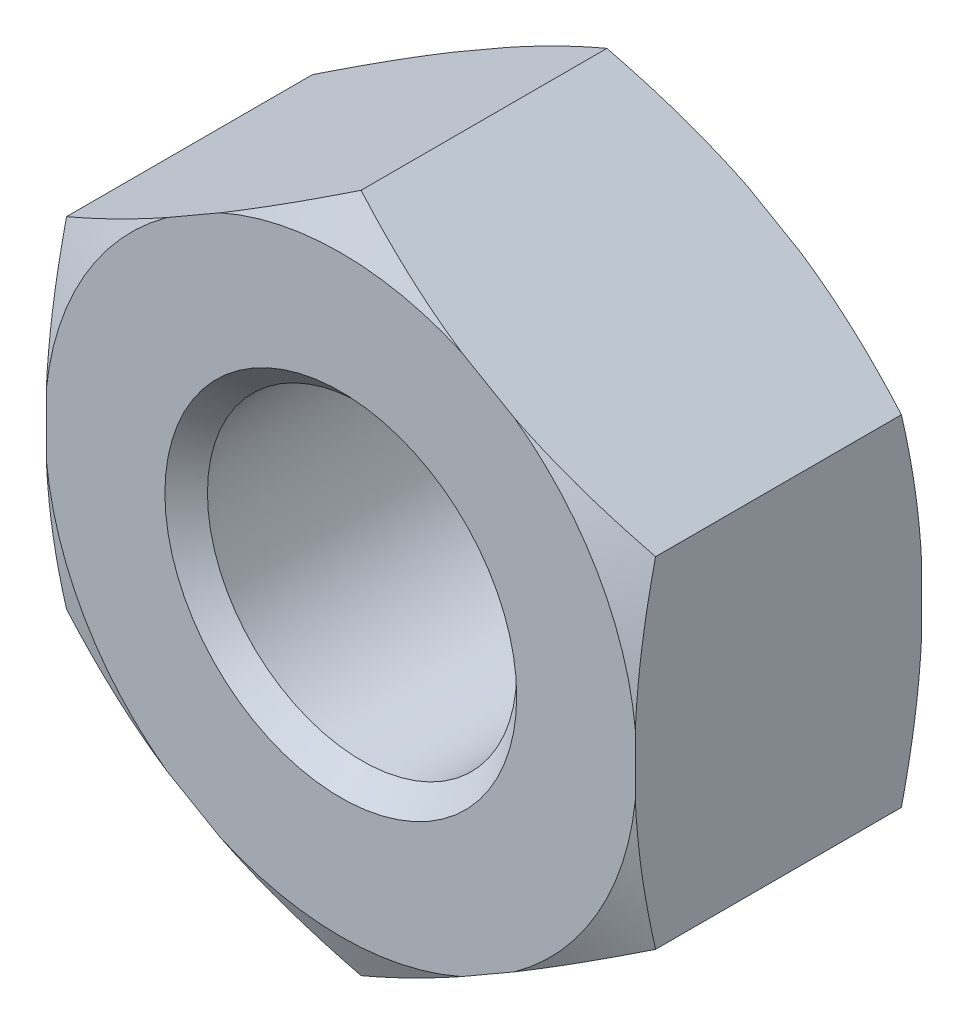
SolidWorks part; units mm, degrees
ref_plane "정면" through (0, 0, 0) normal (0, 0, 1) x (1, 0, 0)
ref_plane "윗면" through (0, 0, 0) normal (0, 1, 0) x (1, 0, 0)
ref_plane "우측면" through (0, 0, 0) normal (1, 0, 0) x (0, 0, -1)
sketch "스케치1" plane through (0, 0, 0) normal (0, 0, 1) x (1, 0, 0)
  line L1 (0, 4.6188) -> (-4, 2.3094)
  line L2 (-4, 2.3094) -> (-4, -2.3094)
  line L3 (-4, -2.3094) -> (0, -4.6188)
  line L4 (0, -4.6188) -> (4, -2.3094)
  line L5 (4, -2.3094) -> (4, 2.3094)
  line L6 (4, 2.3094) -> (0, 4.6188)
  circle A0 centre (0, 0) radius 2.1
  circle A1 centre (0, 0) radius 4 construction
  dimension "D2" = 4.2
  dimension "D1" = 8
extrude "보스-돌출1" add sketch "스케치1" along normal blind 3.89
sketch "스케치3" plane through (0, 0, 0) normal (0, 1, 0) x (1, 0, 0)
  line L0 (2.09, 0.001) -> (2.09, -0.299)
  line L1 (2.1, 0) -> (-2.1, 0) construction
  line L2 (0, 0) -> (4, 0) construction
  line L3 (2.09, -0.299) -> (2.39, 0.001)
  line L4 (2.39, 0.001) -> (2.09, 0.001)
  line L5 (4, 0.01) -> (4.65, 0.01)
  line L6 (4, -3.89) -> (4, 0) construction
  line L7 (4.65, 0.01) -> (4.65, -0.29)
  line L8 (4.65, -0.29) -> (4, 0.01)
  line L9 (4, -1.945) -> (0, -1.945) construction
  line L10 (0, -1.945) -> (0, 0) construction
  line L11 (4.65, -3.6) -> (4, -3.9)
  line L12 (4.65, -3.9) -> (4.65, -3.6)
  line L13 (4, -3.9) -> (4.65, -3.9)
  line L14 (2.39, -3.891) -> (2.09, -3.891)
  line L15 (2.09, -3.591) -> (2.39, -3.891)
  line L16 (2.09, -3.891) -> (2.09, -3.591)
  dimension "D1" = 0.3
  dimension "D2" = 0.3
  dimension "D3" = 0.01
  dimension "D4" = 0.65
  dimension "D5" = 0.001
  dimension "D6" = 2.09
  dimension "D7" = 0.65
  dimension "D8" = 0.3
revolve "컷-회전3" cut sketch "스케치3" angle 360 about L10
